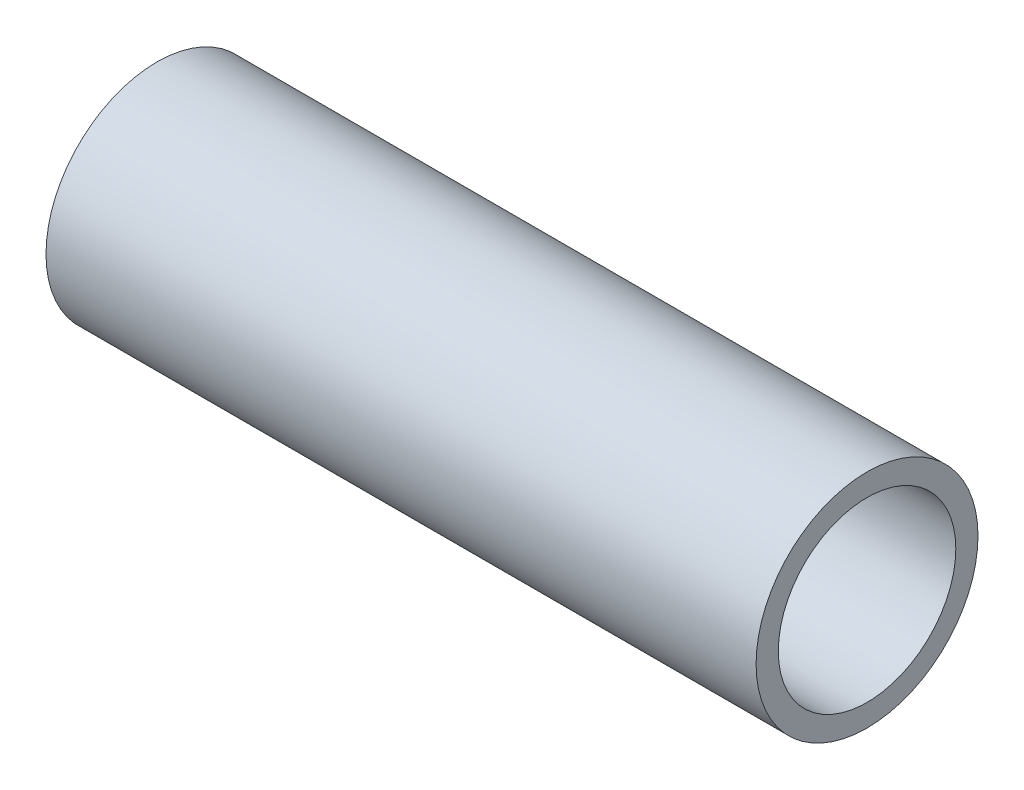
SolidWorks part; units mm, degrees
material "Acrylic (Medium-high impact)"
ref_plane "Front" through (0, 0, 0) normal (0, 0, 1) x (1, 0, 0)
ref_plane "Top" through (0, 0, 0) normal (0, 1, 0) x (1, 0, 0)
ref_plane "Right" through (0, 0, 0) normal (1, 0, 0) x (0, 0, -1)
sketch "Sketch1" plane through (0, 0, 0) normal (1, 0, 0) x (0, 0, -1)
  circle A0 centre (0, 0) radius 15.875
  circle A1 centre (0, 0) radius 12.7
  point P4 (15.875, 0)
  point P5 (12.7, 0)
  dimension "OD" = 31.75
  dimension "ID" = 25.4
  dimension "Wall" = 3.175
extrude "Extrude1" add sketch "Sketch1" along normal mid plane 101.6
